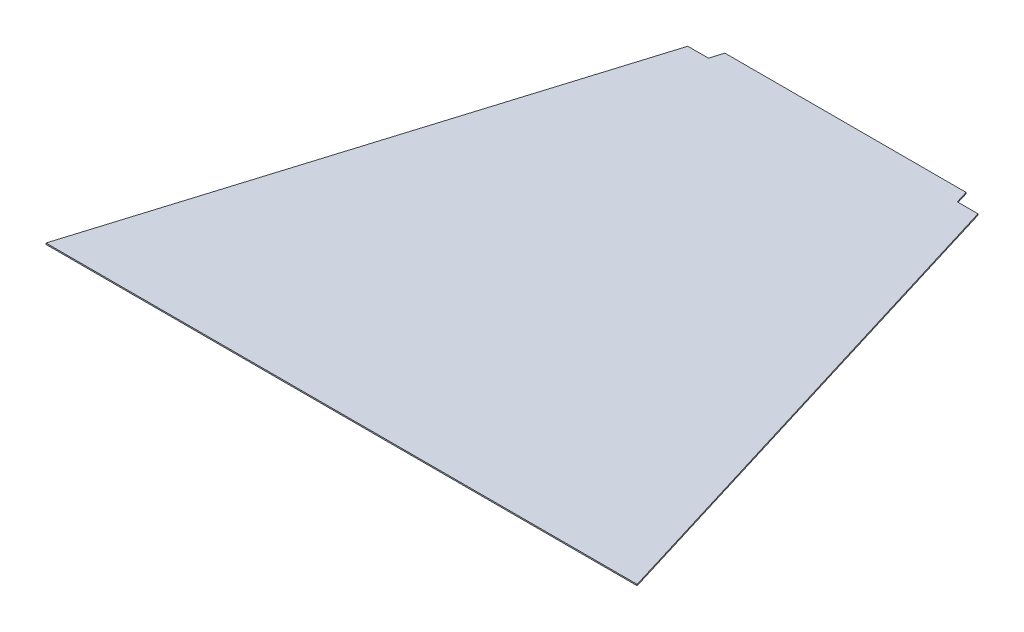
SolidWorks part; units mm, degrees
material "6061 Alloy"
ref_plane "Front Plane" through (0, 0, 0) normal (0, 0, 1) x (1, 0, 0)
ref_plane "Top Plane" through (0, 0, 0) normal (0, 1, 0) x (1, 0, 0)
ref_plane "Right Plane" through (0, 0, 0) normal (1, 0, 0) x (0, 0, -1)
sketch "Sketch1" plane through (0, 0, 0) normal (0, 1, 0) x (1, 0, 0)
  line L1 (-4.5843, 0) -> (-4.5843, -635) construction
  line L2 (-186.4008, 16.1336) -> (-374.9163, -599.4016)
  line L3 (177.2323, 16.1336) -> (365.7477, -599.4016)
  line L4 (-374.9163, -599.4016) -> (365.7477, -599.4016)
  line L6 (-186.4008, 16.1336) -> (-160.4928, 16.1336)
  line L7 (151.3243, 16.1336) -> (177.2323, 16.1336)
  line L8 (-160.4928, 16.1336) -> (-155.6581, 31.9199)
  line L9 (151.3243, 16.1336) -> (146.4895, 31.9199)
  line L10 (-155.6581, 31.9199) -> (146.4895, 31.9199)
  point P4 (0, 0)
  point P12 (-4.5843, 0)
  dimension "D1" = 72.972
  dimension "D2" = 740.664
  dimension "D3" = 643.756
extrude "Boss-Extrude1" add sketch "Sketch1" along normal blind 1.5875
sketch "Sketch2" plane through (0, 0, 0) normal (0, -1, 0) x (1, 0, 0)
  line L0 (-4.5843, -31.9199) -> (-4.5843, 599.4016) construction
  line L1 (146.4895, -31.9199) -> (-155.6581, -31.9199) construction
  line L2 (-374.9163, 599.4016) -> (365.7477, 599.4016) construction
